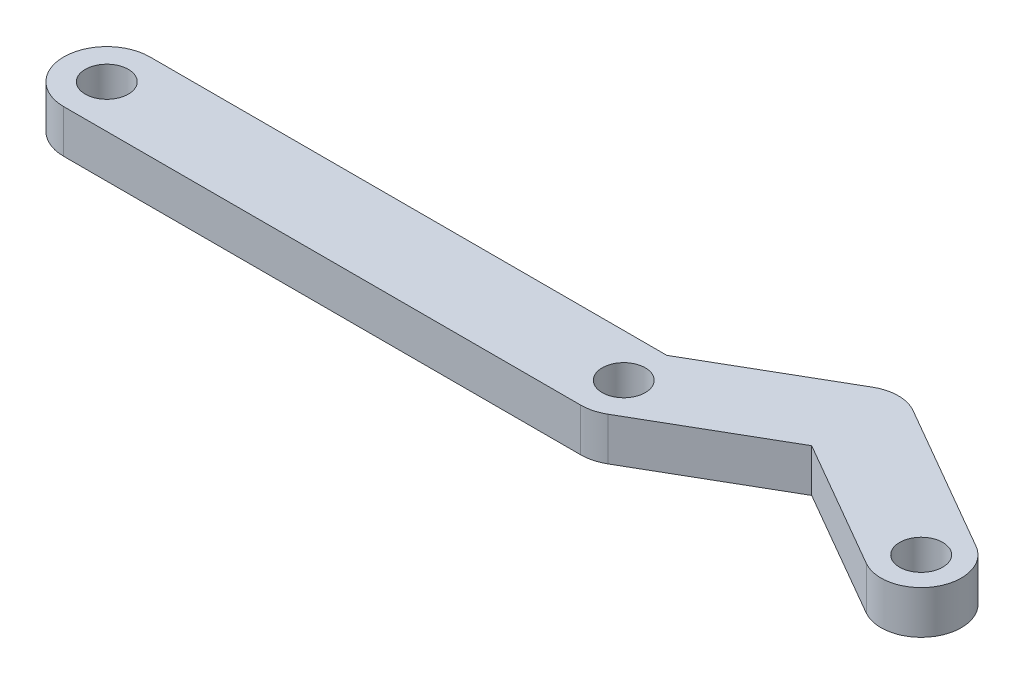
SolidWorks part; units mm, degrees
ref_plane "Front Plane" through (0, 0, 0) normal (0, 0, 1) x (1, 0, 0)
ref_plane "Top Plane" through (0, 0, 0) normal (0, 1, 0) x (1, 0, 0)
ref_plane "Right Plane" through (0, 0, 0) normal (1, 0, 0) x (0, 0, -1)
sketch "Sketch1" plane through (0, 0, 0) normal (0, 1, 0) x (1, 0, 0)
  line L0 (0, 0) -> (-76.2, 0) construction
  line L1 (0, -6.35) -> (-76.2, -6.35)
  line L2 (0, 6.35) -> (-76.2, 6.35)
  arc A0 (0, -6.35) -> (0, 6.35) centre (0, 0) ccw
  arc A1 (-76.2, 6.35) -> (-76.2, -6.35) centre (-76.2, 0) ccw
  circle A2 centre (-76.2, 0) radius 3.175
  circle A3 centre (0, 0) radius 3.175
  point P3 (-38.1, 0)
  dimension "D1" = 6.35
  dimension "D3" = 6.35
  dimension "D2" = 76.2
extrude "Boss-Extrude1" add sketch "Sketch1" along normal blind 6.35
sketch "Sketch2" plane through (0, 6.35, 0) normal (0, 1, 0) x (1, 0, 0)
  line L0 (0, 6.35) -> (-76.2, 6.35) construction
  line L1 (3.175, -5.4993) -> (25.172, 7.2007)
  line L2 (0, 6.35) -> (19.2474, 17.4625)
  line L3 (19.2474, 17.4625) -> (25.172, 7.2007) construction
  arc A0 (0, 6.35) -> (3.175, -5.4993) centre (0, 0) cw
  arc A1 (0, -6.35) -> (0, 6.35) centre (0, 0) ccw construction
  arc A2 (19.2474, 17.4625) -> (25.172, 7.2007) centre (22.2097, 12.3316) cw
  dimension "D1" = 150
  dimension "D2" = 25.4
extrude "Boss-Extrude2" add sketch "Sketch2" against normal up to surface (6.35 mm away) up to face at (-38.1, 0, 0)
sketch "Sketch3" plane through (0, 6.35, 0) normal (0, 1, 0) x (1, 0, 0)
  line L0 (25.172, 17.4625) -> (47.1691, 4.7625)
  line L1 (25.172, 7.2007) -> (22.2097, 5.4904)
  line L2 (3.175, -5.4993) -> (25.172, 7.2007) construction
  line L3 (22.2097, 5.4904) -> (41.2445, -5.4993)
  line L4 (41.2445, -5.4993) -> (47.1691, 4.7625) construction
  line L5 (0, 6.35) -> (5.9246, -3.9118) construction
  arc A0 (25.172, 7.2007) -> (25.172, 17.4625) centre (22.2097, 12.3316) ccw
  arc A1 (47.1691, 4.7625) -> (41.2445, -5.4993) centre (44.2068, -0.3684) cw
  arc A2 (25.172, 7.2007) -> (19.2474, 17.4625) centre (22.2097, 12.3316) ccw construction
  circle A3 centre (44.2068, -0.3684) radius 3.175
  circle A5 centre (0, 0) radius 3.175 construction
  point P20 (22.2097, 12.3316)
  point P21 (22.2097, 12.3316)
  dimension "D1" = 25.4
  dimension "D2" = 120
extrude "Boss-Extrude3" add sketch "Sketch3" against normal up to surface (6.35 mm away) up to face at (-15.1384, 0, -3.131)
